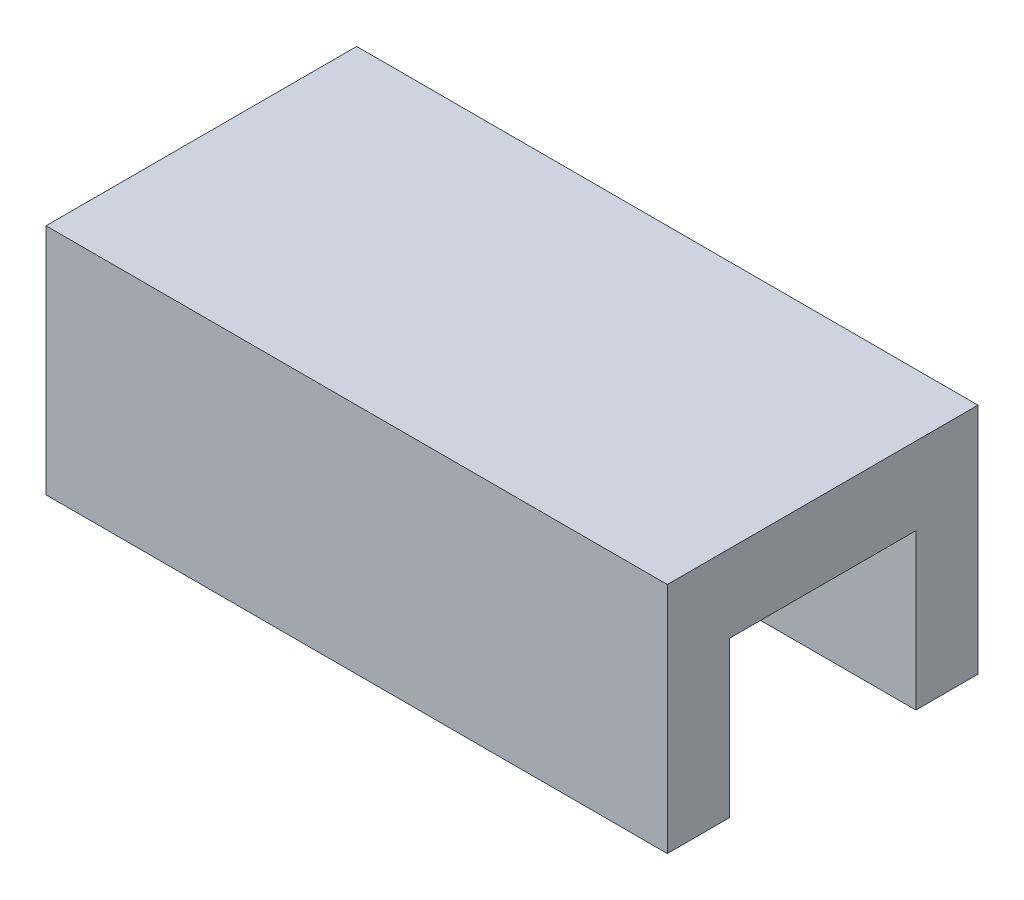
SolidWorks part; units mm, degrees
ref_plane "前视基准面" through (0, 0, 0) normal (0, 0, 1) x (1, 0, 0)
ref_plane "上视基准面" through (0, 0, 0) normal (0, 1, 0) x (1, 0, 0)
ref_plane "右视基准面" through (0, 0, 0) normal (1, 0, 0) x (0, 0, -1)
other "Configuration Table"
sketch "草图1" plane through (0, 0, 0) normal (1, 0, 0) x (0, 0, -1)
  line L0 (4, 0) -> (4, 10)
  line L5 (0, 0) -> (4, 0)
  line L6 (0, 0) -> (0, 15)
  line L7 (0, 15) -> (20, 15)
  line L8 (20, 0) -> (20, 15)
  line L9 (4, 10) -> (16, 10)
  line L10 (16, 10) -> (16, 0)
  line L11 (16, 0) -> (20, 0)
  dimension "D1" = 20
  dimension "D2" = 15
  dimension "D3" = 10
  dimension "D4" = 12
  dimension "D5" = 4
extrude "凸台-拉伸1" add sketch "草图1" along normal blind 40
